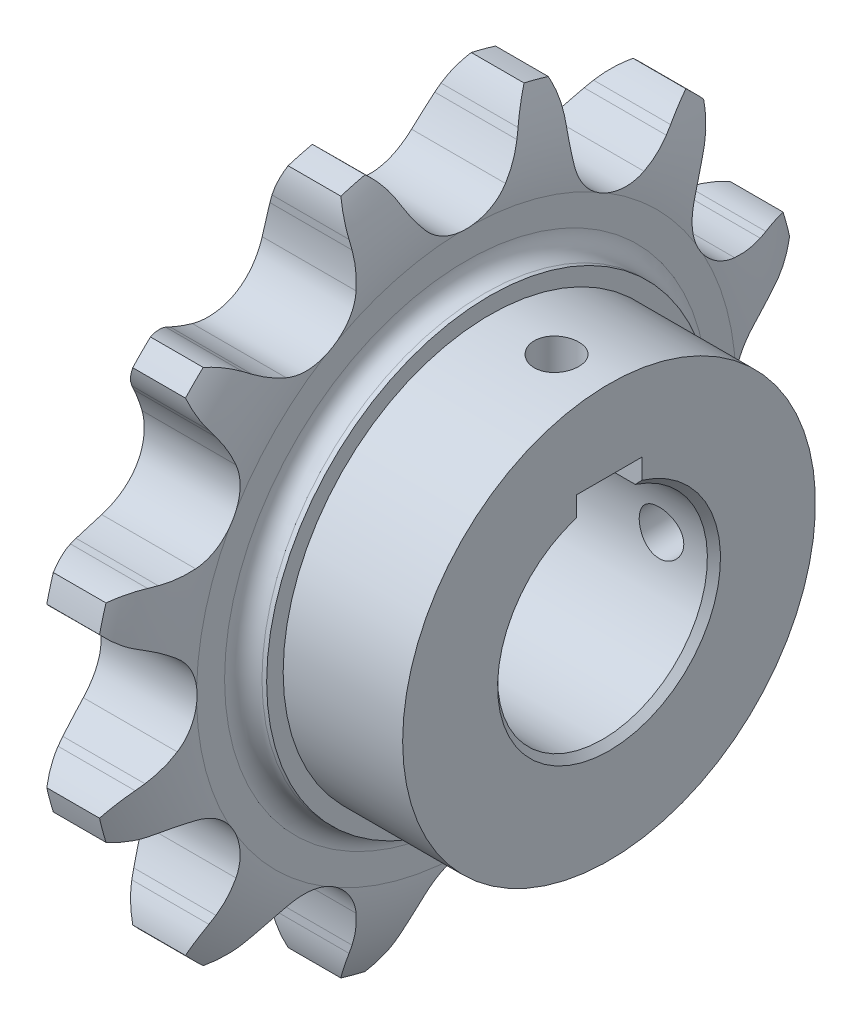
SolidWorks part; units mm, degrees
ref_plane "前视基准面" through (0, 0, 0) normal (0, 0, 1) x (1, 0, 0)
ref_plane "上视基准面" through (0, 0, 0) normal (0, 1, 0) x (1, 0, 0)
ref_plane "右视基准面" through (0, 0, 0) normal (1, 0, 0) x (0, 0, -1)
sketch "草图1" plane through (0, 0, 0) normal (0, 0, 1) x (1, 0, 0)
  line L0 (-12.7, 0) -> (12.7, 0) construction
  line L1 (-10.8883, 16) -> (-10.8883, 34)
  line L2 (-10.8883, 34) -> (-10.1754, 34)
  line L3 (-7.3238, 36.8516) -> (-7.3237, 41.129)
  line L4 (-4.0217, 54) -> (4.0217, 54)
  line L5 (7.3237, 41.129) -> (7.3238, 36.8516)
  line L6 (10.1754, 34) -> (10.8883, 34)
  line L7 (10.8883, 34) -> (10.8883, 16)
  line L8 (10.8883, 16) -> (-10.8883, 16)
  line L9 (0, 0) -> (0, 54) construction
  line L10 (-6.1635, 49.069) -> (6.1635, 49.069) construction
  line L11 (-6.1635, -49.069) -> (6.1635, -49.069) construction
  line L12 (12.7, 0) -> (24.7, 0) construction
  line L13 (-7.3237, 41.129) -> (3.7984, 41.129) construction
  line L14 (-7.3237, -41.129) -> (3.7984, -41.129) construction
  line L15 (24.7, 0) -> (40.58, 0) construction
  line L16 (40.58, 0) -> (64.71, 0) construction
  line L17 (64.71, 0) -> (80.46, 0) construction
  line L18 (80.46, 0) -> (109.75, 0) construction
  arc A0 (-4.0217, 54) -> (-7.3237, 41.129) centre (18.0739, 41.4724) ccw
  arc A1 (4.0217, 54) -> (7.3237, 41.129) centre (-18.0739, 41.4724) cw
  arc A2 (7.3238, 36.8516) -> (10.1754, 34) centre (10.1754, 36.8516) ccw
  arc A3 (-10.1754, 34) -> (-7.3238, 36.8516) centre (-10.1754, 36.8516) ccw
  point P30 (7.3237, 34)
  point P33 (-7.3237, 34)
  dimension "D1" = 7.129
  dimension "rx" = 25.4
  dimension "D3" = 2.8516
  dimension "d" = 98.1381
  dimension "p" = 25.4
  dimension "z" = 12
  dimension "da" = 108
  dimension "df" = 82.2581
  dimension "dr" = 15.88
  dimension "dk" = 32
  dimension "dg" = 68
  dimension "h" = 24.13
  dimension "bf1" = 14.6475
  dimension "b1" = 15.75
  dimension "ba" = 3.302
  dimension "D2" = 3.5645
  dimension "pt" = 29.29
revolve "旋转1" add sketch "草图1" angle 360 about L0
sketch "草图2" plane through (0, 0, 0) normal (1, 0, 0) x (0, 0, -1)
  line L0 (0, 0) -> (0, 54) construction
  line L1 (0, 0) -> (-13.9762, 52.16) construction
  line L2 (0, 0) -> (-27, 46.7654) construction
  line L3 (6.1511, 43.9076) -> (8.5213, 41.9188) construction
  line L4 (8.7965, 47.9297) -> (-9.7318, 57.235) construction
  line L5 (0, 0) -> (13.9762, 52.16) construction
  line L6 (8.7965, 47.9297) -> (9.3552, 49.0422)
  line L7 (-8.7965, 47.9297) -> (-9.3552, 49.0422)
  circle A0 centre (0, 0) radius 54 construction
  arc A1 (6.1511, 43.9076) -> (-6.1511, 43.9076) centre (0, 49.069) cw
  arc A2 (6.1511, 43.9076) -> (8.7965, 47.9297) centre (-9.7318, 57.235) ccw
  arc A3 (12.1196, 52.6224) -> (9.3552, 49.0422) centre (19.9406, 43.726) ccw
  arc A4 (-6.1511, 43.9076) -> (-8.7965, 47.9297) centre (9.7318, 57.235) cw
  arc A5 (-12.1196, 52.6224) -> (-9.3552, 49.0422) centre (-19.9406, 43.726) cw
  arc A7 (12.1196, 52.6224) -> (-12.1196, 52.6224) centre (0, 0) ccw
  dimension "r1" = 8.0297
  dimension "r3" = 11.8454
  dimension "D1" = 30
  dimension "D2" = 15
  dimension "α/2" = 50
  dimension "M" = 9.7318
  dimension "T" = 8.166
  dimension "β" = 13.333
  dimension "γ/2" = 11.667
  dimension "bc" = 1.2448
extrude "切除-拉伸1" cut sketch "草图2" against normal mid plane 21.7765
pattern_circular "阵列(圆周)1" count 12 over 360 about axis through (0, 0, 0) along (1, 0, 0) of "切除-拉伸1"
sketch "草图3" plane through (0, 0, 0) normal (0, 0, 1) x (1, 0, 0)
  line L0 (10.8883, 16) -> (29.1117, 16)
  line L3 (29.1117, 16) -> (29.1117, 31.4814)
  line L4 (29.1117, 31.4814) -> (10.8883, 31.4814)
  line L5 (10.8883, 31.4814) -> (10.8883, 16)
  line L6 (0, 0) -> (9.5, 0) construction
  line L8 (-10.8883, 34) -> (-10.8883, -34) construction
  dimension "h" = 15.4814
  dimension "K" = 9.5
  dimension "L" = 40
revolve "旋转2" add sketch "草图3" angle 360 about L6
sketch "草图4" plane through (-10.8883, 0, 0) normal (-1, 0, 0) x (0, 0, 1)
  line L1 (-5, 15.1987) -> (5, 15.1987)
  line L2 (-5, 15.1987) -> (-5, 19.3)
  line L3 (-5, 19.3) -> (5, 19.3)
  line L4 (5, 15.1987) -> (5, 19.3)
  circle A0 centre (0, 0) radius 16 construction
  point P6 (1.7, 19.3)
  dimension "D1" = 19.3
  dimension "键槽宽度" = 10
  dimension "t1" = 3.3
extrude "切除-拉伸2" cut sketch "草图4" against normal through all
chamfer "倒角1" distance 1 angle 45 1 edges at (-10.8883, -16, 0)
chamfer "倒角3" distance 1 angle 45 1 edges at (29.1117, -16, 0)
hole_wizard "M8x1.25 螺纹孔1" positions "草图9" profile "草图8" tap size "M8x1.25" standard "Ansi Metric"
sketch "草图9" plane through (-14.5559, 0, 0) normal (0, -1, 0) x (-1, 0, 0)
  line L0 (-14.5559, 0) -> (-43.6676, 0) construction
  line L1 (-43.6676, 31.4814) -> (-43.6676, -31.4814) construction
  point P0 (-35.6676, 0)
  dimension "D1" = 8
cosmetic thread "孔螺蚊线1" parameters "D2"=8
sketch "草图8" plane through (21.1117, 0, 0) normal (1, 0, 0) x (0, 0, -1)
  line L0 (0, 0) -> (0, 52.6224)
  line L1 (0, 52.6224) -> (3.4, 52.6224)
  line L2 (3.4, 52.6224) -> (3.4, 0)
  line L5 (3.4, 0) -> (0, 0)
  line L11 (0, -6.35) -> (0, 107.95) construction
  dimension "通孔螺纹孔钻头直径" = 6.8
  dimension "通孔螺纹孔钻头深度" = 52.6224
pattern_circular "阵列(圆周)2" count 2 every 90 about axis through (-12.7, 0, 0) along (-1, 0, 0) of "M8x1.25 螺纹孔1"
